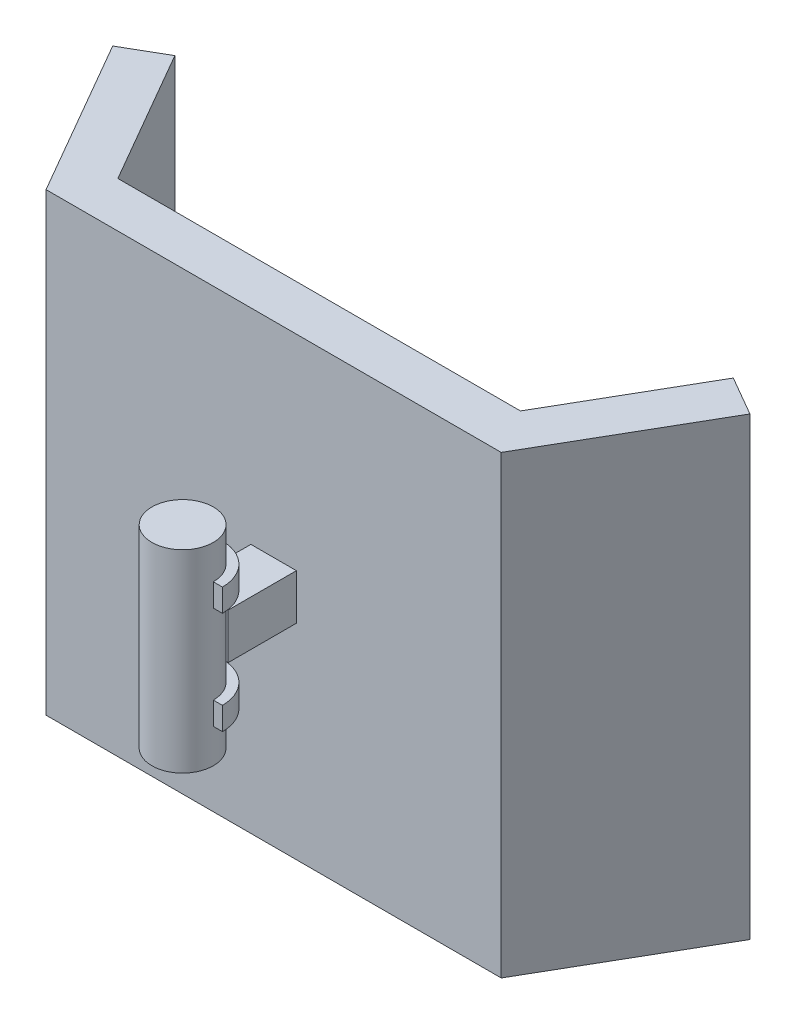
SolidWorks part; units mm, degrees
ref_plane "前视基准面" through (0, 0, 0) normal (0, 0, 1) x (1, 0, 0)
ref_plane "上视基准面" through (0, 0, 0) normal (0, 1, 0) x (1, 0, 0)
ref_plane "右视基准面" through (0, 0, 0) normal (1, 0, 0) x (0, 0, -1)
other "Configuration Table"
sketch "草图1" plane through (0, 0, 0) normal (0, 0, 1) x (1, 0, 0)
  line L1 (-1, -1) -> (1, -1)
  line L2 (-1, -1) -> (-1, 1)
  line L3 (-1, 1) -> (1, 1)
  line L4 (1, -1) -> (1, 1)
  line L5 (-1, -1) -> (1, 1) construction
  line L6 (-1, 1) -> (1, -1) construction
  point P0 (0, 0)
  dimension "D1" = 2
extrude "凸台-拉伸1" add sketch "草图1" along normal blind 3
sketch "草图2" plane through (0, 1, 0) normal (0, 1, 0) x (1, 0, 0)
  line L0 (0, -3) -> (0, 0) construction
  line L1 (1, -3) -> (-1, -3) construction
  circle A0 centre (0, -4) radius 1.35
  dimension "D1" = 1
  dimension "D2" = 2.7
extrude "凸台-拉伸2" add sketch "草图2" along normal blind 3.25 and the other way blind 5.25
ref_plane "基准面1" through (0, -2.75, 0) normal (0, -1, 0) x (-1, 0, 0)
sketch "草图6" plane through (0, -2.75, 0) normal (0, -1, 0) x (-1, 0, 0)
  line L0 (-1.75, -4) -> (1.75, -4)
  arc A0 (1.75, -4) -> (-1.75, -4) centre (0, -4) ccw
  dimension "D1" = 3.5
extrude "凸台-拉伸5" add sketch "草图6" against normal blind 1
ref_plane "基准面2" through (0, 2.75, 0) normal (0, 1, 0) x (1, 0, 0)
sketch "草图7" plane through (0, 2.75, 0) normal (0, 1, 0) x (1, 0, 0)
  line L0 (1.75, -4) -> (-1.75, -4)
  arc A1 (1.75, -4) -> (-1.75, -4) centre (0, -4) ccw
extrude "凸台-拉伸6" add sketch "草图7" against normal blind 1
sketch "草图12" plane through (0, 0, 0) normal (0, 1, 0) x (1, 0, 0)
  line L0 (10, 0) -> (-10, 0)
  line L1 (-10, 0) -> (-14, 6.9282)
  line L2 (-14, 6.9282) -> (-12.2679, 7.9282)
  line L3 (-12.2679, 7.9282) -> (-8.8453, 2)
  line L4 (-8.8453, 2) -> (8.8453, 2)
  line L5 (0, 2) -> (0, 0) construction
  line L6 (12.2679, 7.9282) -> (8.8453, 2)
  line L7 (14, 6.9282) -> (12.2679, 7.9282)
  line L8 (10, 0) -> (14, 6.9282)
  dimension "D1" = 2
  dimension "D2" = 20
  dimension "D3" = 8
  dimension "D4" = 2
  dimension "D5" = 120
extrude "凸台-拉伸7" add sketch "草图12" along normal blind 10 and the other way blind 10
